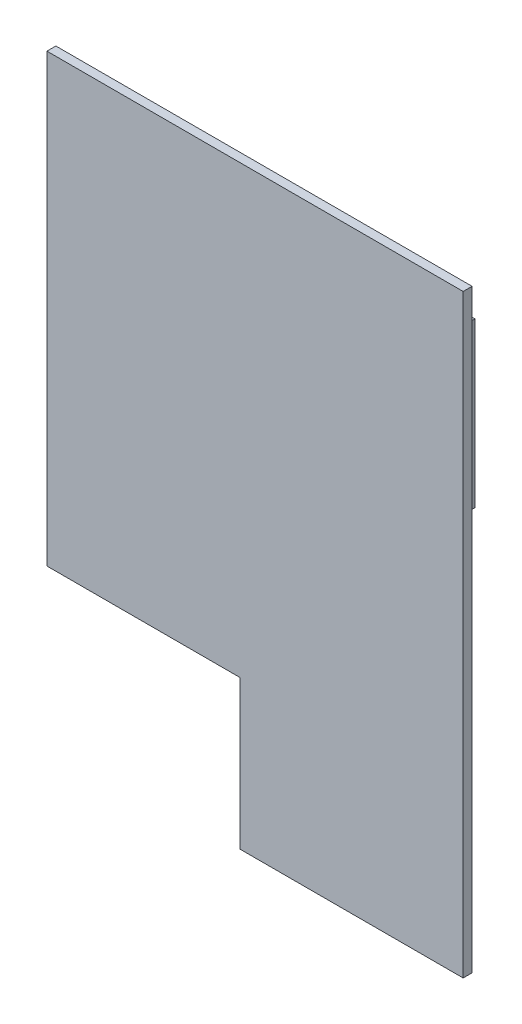
SolidWorks part; units mm, degrees
ref_plane "前视基准面" through (0, 0, 0) normal (0, 0, 1) x (1, 0, 0)
ref_plane "上视基准面" through (0, 0, 0) normal (0, 1, 0) x (1, 0, 0)
ref_plane "右视基准面" through (0, 0, 0) normal (1, 0, 0) x (0, 0, -1)
sketch "草图1" plane through (0, 0, 0) normal (0, 0, 1) x (1, 0, 0)
  line L1 (0, 0) -> (140, 0)
  line L2 (0, 0) -> (0, -200)
  line L3 (0, -200) -> (140, -200)
  line L4 (140, 0) -> (140, -200)
  dimension "D1" = 140
  dimension "D2" = 200
extrude "凸台-拉伸1" add sketch "草图1" along normal blind 3
sketch "草图2" plane through (0, 0, 0) normal (0, 0, -1) x (-1, 0, 0)
  line L0 (0, -200) -> (-140, -200) construction
  line L1 (-65, -200) -> (0, -200)
  line L2 (-65, -200) -> (-65, -150)
  line L3 (-65, -150) -> (0, -150)
  line L4 (0, -200) -> (0, -150)
  line L5 (0, 0) -> (0, -200) construction
  dimension "D1" = 65
  dimension "D2" = 50
extrude "切除-拉伸1" cut sketch "草图2" against normal blind 10
sketch "草图4" plane through (0, 0, 3) normal (0, 0, 1) x (1, 0, 0)
  line L1 (5, -27) -> (8, -27)
  line L3 (5, -82) -> (8, -82)
  line L4 (8, -27) -> (8, -82)
  line L5 (8, -116.1645) -> (8, -6.1645) construction
  line L6 (140, 0) -> (0, 0) construction
  line L8 (8, -27) -> (5, -27)
  line L9 (8, -27) -> (8, -82)
  line L10 (8, -82) -> (5, -82)
  line L11 (5, -27) -> (5, -82)
  dimension "D1" = 27
  dimension "D3" = 3
extrude "凸台-拉伸4" add sketch "草图4" along normal blind 18 contours L1 L11 L3 L4
sketch "草图5" plane through (5, 0, 0) normal (-1, 0, 0) x (0, 0, 1)
  circle A0 centre (13, -76.1645) radius 1.5 construction
  circle A1 centre (13, -76.1645) radius 1.5
  circle A2 centre (13, -36.1645) radius 1.5 construction
  circle A3 centre (13, -36.1645) radius 1.5
extrude "切除-拉伸2" cut sketch "草图5" against normal up to next
sketch "草图6" plane through (128, 0, 0) normal (1, 0, 0) x (0, 0, -1)
  line L4 (-3, -82) -> (-3, -27)
  line L5 (-21, -82) -> (-3, -82)
  line L6 (-21, -27) -> (-21, -82)
  line L7 (-3, -27) -> (-21, -27)
  line L8 (-3, -82) -> (-3, -27)
  line L9 (-21, -82) -> (-3, -82)
  line L10 (-21, -27) -> (-21, -82)
  line L11 (-3, -27) -> (-21, -27)
  circle A0 centre (-13, -76.1645) radius 1.5 construction
  circle A1 centre (-13, -76.1645) radius 1.5
  circle A2 centre (-13, -36.1645) radius 1.5 construction
  circle A3 centre (-13, -36.1645) radius 1.5
  dimension "D1" = 0
extrude "凸台-拉伸6" add sketch "草图6" along normal blind 3
mirror "镜向1" about plane through (0, 0, 0) normal (0, 0, 1) of "凸台-拉伸1", "切除-拉伸1", "凸台-拉伸4", "切除-拉伸2", "凸台-拉伸6"
sketch "草图7" plane through (140, 0, 0) normal (1, 0, 0) x (0, 0, -1)
  line L1 (0, 0) -> (-55.809, 0)
  line L2 (0, 0) -> (0, -208.3451)
  line L3 (0, -208.3451) -> (-55.809, -208.3451)
  line L4 (-55.809, 0) -> (-55.809, -208.3451)
extrude "切除-拉伸3" cut sketch "草图7" against normal up to next
sketch "草图8" plane through (0, 0, -3) normal (0, 0, -1) x (-1, 0, 0)
  line L1 (-128, -27) -> (-123, -27) construction
  line L2 (-128, -27) -> (-128, -82) construction
  line L3 (-128, -82) -> (-123, -82) construction
  line L4 (-123, -27) -> (-123, -82) construction
  line L5 (-123, -27) -> (-120, -27)
  line L6 (-123, -27) -> (-123, -82)
  line L7 (-123, -82) -> (-120, -82)
  line L8 (-120, -27) -> (-120, -82)
  dimension "D1" = 5
  dimension "D2" = 3
extrude "凸台-拉伸7" add sketch "草图8" along normal up to surface (18 mm away) up to face at (6.5, -54.5, -21)
sketch "草图9" plane through (120, 0, 0) normal (-1, 0, 0) x (0, 0, 1)
  circle A0 centre (-13, -36.1645) radius 1.5 construction
  circle A1 centre (-13, -36.1645) radius 1.5
  circle A2 centre (-13, -76.1645) radius 1.5 construction
  circle A3 centre (-13, -76.1645) radius 1.5
extrude "切除-拉伸4" cut sketch "草图9" against normal blind 10
sketch "草图10" plane through (0, 0, -21) normal (0, 0, -1) x (-1, 0, 0)
  line L4 (-128, -82) -> (-128, -27)
  line L5 (-128, -27) -> (-131, -27)
  line L6 (-131, -27) -> (-131, -82)
  line L7 (-131, -82) -> (-128, -82)
  line L8 (-128, -82) -> (-128, -27)
  line L9 (-128, -27) -> (-131, -27)
  line L10 (-131, -27) -> (-131, -82)
  line L11 (-131, -82) -> (-128, -82)
  dimension "D1" = 0
extrude "切除-拉伸5" cut sketch "草图10" against normal up to surface (18 mm away) up to face at (129.5, -54.5, -3)
